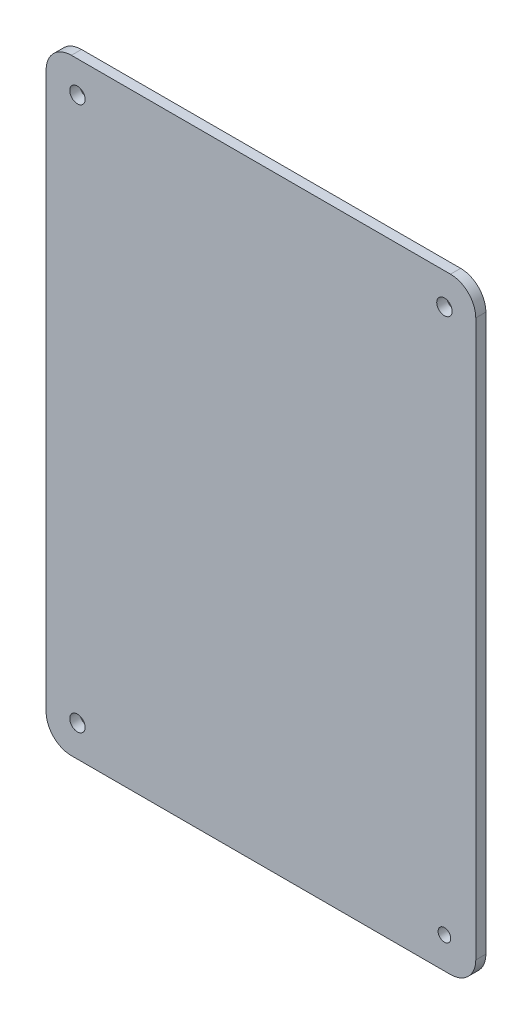
SolidWorks part; units mm, degrees
ref_plane "Front Plane" through (0, 0, 0) normal (0, 0, 1) x (1, 0, 0)
ref_plane "Top Plane" through (0, 0, 0) normal (0, 1, 0) x (1, 0, 0)
ref_plane "Right Plane" through (0, 0, 0) normal (1, 0, 0) x (0, 0, -1)
sketch "Sketch1" plane through (0, 0, 0) normal (0, 0, 1) x (1, 0, 0)
  line L0 (-37.5, 57.2608) -> (37.5, 57.2608) construction
  line L1 (-42.5, -57.7392) -> (-42.5, 52.2608) construction
  line L2 (-37.5, -62.7392) -> (37.5, -62.7392) construction
  line L3 (42.5, -57.7392) -> (42.5, 52.2608) construction
  line L4 (-37.5, 57.2608) -> (37.5, 57.2608)
  line L5 (-42.5, -57.7392) -> (-42.5, 52.2608)
  line L6 (-37.5, -62.7392) -> (37.5, -62.7392)
  line L7 (42.5, -57.7392) -> (42.5, 52.2608)
  arc A0 (42.5, 52.2608) -> (37.5, 57.2608) centre (37.5, 52.2608) ccw construction
  arc A1 (-37.5, 57.2608) -> (-42.5, 52.2608) centre (-37.5, 52.2608) ccw construction
  arc A2 (-42.5, -57.7392) -> (-37.5, -62.7392) centre (-37.5, -57.7392) ccw construction
  arc A3 (37.5, -62.7392) -> (42.5, -57.7392) centre (37.5, -57.7392) ccw construction
  circle A4 centre (36.3, -56.5392) radius 1.25 construction
  circle A5 centre (36.3, 51.0608) radius 1.525 construction
  circle A6 centre (-36.3, 51.0608) radius 1.525 construction
  circle A7 centre (-36.3, -56.5392) radius 1.525 construction
  arc A8 (42.5, 52.2608) -> (37.5, 57.2608) centre (37.5, 52.2608) ccw
  arc A9 (-37.5, 57.2608) -> (-42.5, 52.2608) centre (-37.5, 52.2608) ccw
  arc A10 (-42.5, -57.7392) -> (-37.5, -62.7392) centre (-37.5, -57.7392) ccw
  arc A11 (37.5, -62.7392) -> (42.5, -57.7392) centre (37.5, -57.7392) ccw
  circle A12 centre (36.3, -56.5392) radius 1.25
  circle A13 centre (36.3, 51.0608) radius 1.525
  circle A14 centre (-36.3, 51.0608) radius 1.525
  circle A15 centre (-36.3, -56.5392) radius 1.525
  dimension "D1" = 72.6
extrude "Boss-Extrude1" add sketch "Sketch1" along normal blind 2
sketch "Sketch3" plane through (0, 0, 0) normal (0, 0, -1) x (-1, 0, 0)
  line L0 (-37.5, 57.2608) -> (37.5, 57.2608) construction
  line L1 (42.5, 52.2608) -> (42.5, -57.7392) construction
  circle A0 centre (-19.5, 36.2608) radius 2
  circle A1 centre (19.5, 36.2608) radius 2
  circle A2 centre (19.5, -2.7392) radius 2
  circle A3 centre (-19.5, -2.7392) radius 2
  dimension "D1" = 4
  dimension "D2" = 39
  dimension "D3" = 39
  dimension "D4" = 39
  dimension "D5" = 23
  dimension "D6" = 21
extrude "Boss-Extrude2" add sketch "Sketch3" along normal blind 8
hole_wizard "M3 Tapped Hole1" positions "Sketch4" profile "Sketch5" tap size "M3" standard "ISO"
sketch "Sketch4" plane through (0, 0, -8) normal (0, 0, -1) x (-1, 0, 0)
  point P0 (-19.5, -2.7392)
  point P3 (-19.5, 36.2608)
  point P6 (19.5, 36.2608)
  point P9 (19.5, -2.7392)
sketch "Sketch5" plane through (19.5, -2.7392, -8) normal (1, 0, 0) x (0, 1, 0)
  line L0 (0, 0) -> (0, 6.7511)
  line L1 (0, 6.7511) -> (1.25, 6)
  line L2 (1.25, 6) -> (1.25, 0.275)
  line L3 (1.25, 0.275) -> (1.525, 0)
  line L5 (1.525, 0) -> (0, 0)
  line L6 (-1.25, 0.275) -> (-1.525, 0) construction
  line L10 (0, 6.7511) -> (-1.25, 6) construction
  line L11 (0, -6.35) -> (0, 107.95) construction
  dimension "Tap Drill Dia." = 2.5
  dimension "Tap Drill Depth" = 6
  dimension "Near C'Sink Dia." = 3.05
  dimension "Near C'Sink Angle" = 90
  dimension "Drill Angle" = 118
cosmetic thread "Hole Thread1" parameters "D1"=6, "D2"=3
cosmetic thread "Hole Thread2" parameters "D1"=6, "D2"=3
cosmetic thread "Hole Thread3" parameters "D1"=6, "D2"=3
cosmetic thread "Hole Thread4" parameters "D1"=6, "D2"=3
fillet "Fillet1" radius 2 4 edges at (-21.5, -2.7392, 0) (-21.5, 36.2608, 0) (17.5, -2.7392, 0) (17.5, 36.2608, 0)
